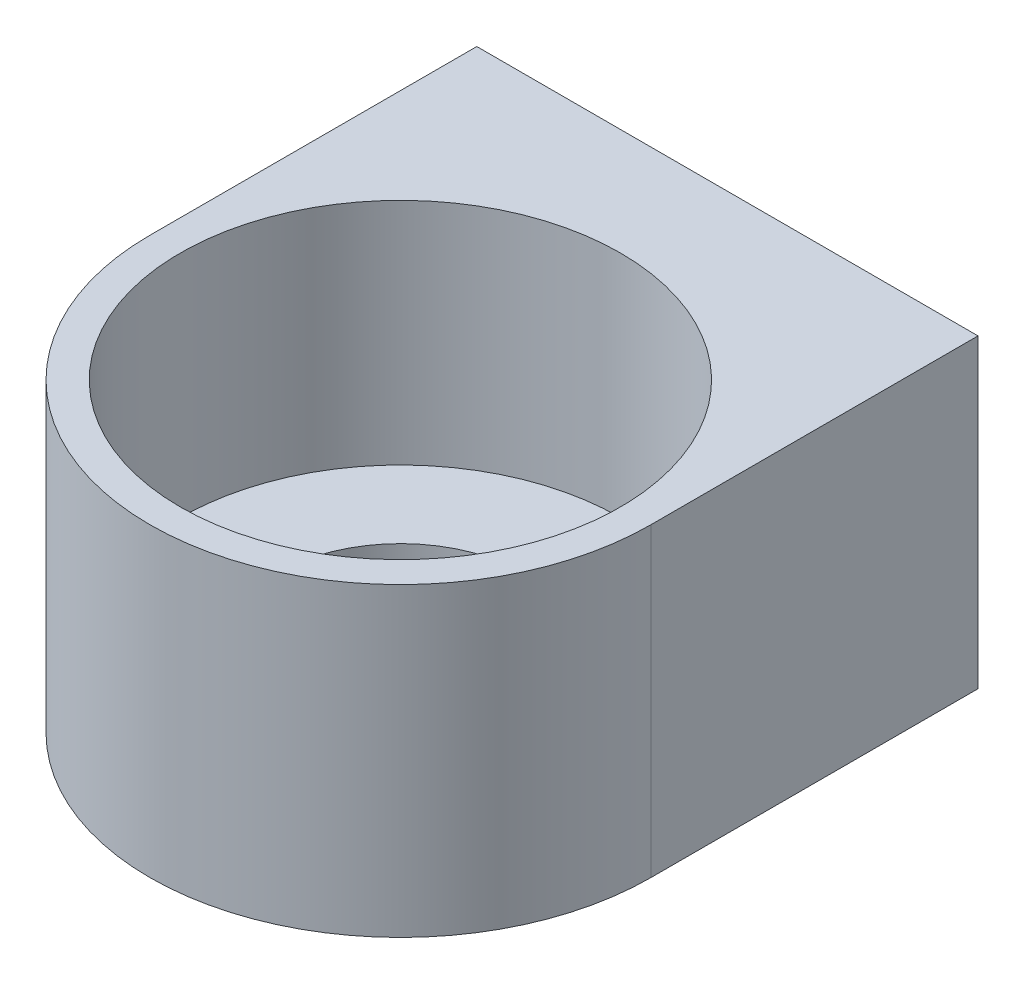
SolidWorks part; units mm, degrees
ref_plane "Front Plane" through (0, 0, 0) normal (0, 0, 1) x (1, 0, 0)
ref_plane "Top Plane" through (0, 0, 0) normal (0, 1, 0) x (1, 0, 0)
ref_plane "Right Plane" through (0, 0, 0) normal (1, 0, 0) x (0, 0, -1)
sketch "Sketch1" plane through (0, 0, 0) normal (0, 1, 0) x (1, 0, 0)
  line L0 (0, 21.4) -> (0, 16.4) construction
  line L2 (-16.4, 0) -> (-16.4, 21.4)
  line L3 (-16.4, 21.4) -> (16.4, 21.4)
  line L4 (16.4, 0) -> (16.4, 21.4)
  circle A0 centre (0, 0) radius 8.1
  circle A1 centre (0, 0) radius 14.4 construction
  arc A2 (-16.4, 0) -> (16.4, 0) centre (0, 0) ccw
  arc A3 (-16.4, 0) -> (16.4, 0) centre (0, 0) cw construction
  dimension "D1" = 16.2
  dimension "D2" = 28.8
  dimension "D3" = 32.8
extrude "Boss-Extrude1" add sketch "Sketch1" along normal blind 100
sketch "Sketch2" plane through (0, 100, 0) normal (0, 1, 0) x (1, 0, 0)
  circle A0 centre (0, 0) radius 14.4
  dimension "D1" = 28.8
extrude "Cut-Extrude1" cut sketch "Sketch2" against normal blind 80
sketch "Sketch3" plane through (0, 100, 0) normal (0, 1, 0) x (1, 0, 0)
  line L0 (0, 14.4) -> (-16.4, 14.4) construction
  line L1 (-16.4, 21.4) -> (-16.4, 0) construction
  line L2 (-16.4, 14.4) -> (-16.4, 0) construction
  line L3 (0, 14.4) -> (0, -16.4) construction
  line L4 (-16.4, 0) -> (-16.4, 14.4)
  line L5 (-16.4, 14.4) -> (16.4, 14.4)
  line L6 (16.4, 0) -> (16.4, 14.4)
  circle A0 centre (0, 0) radius 14.4 construction
  circle A1 centre (0, 0) radius 14.4 construction
  arc A3 (-16.4, 0) -> (16.4, 0) centre (0, 0) ccw
extrude "Cut-Extrude2" cut sketch "Sketch3" against normal blind 80
sketch "Sketch4" plane through (0, 20, 0) normal (0, 1, 0) x (1, 0, 0)
  circle A0 centre (0, 0) radius 14.4
  dimension "D1" = 28.8
extrude "Cut-Extrude3" cut sketch "Sketch4" against normal blind 15
sketch "Sketch8" plane through (0, 0, -14.4) normal (0, 0, 1) x (1, 0, 0)
  line L1 (-16.4, 100) -> (16.4, 100)
  line L2 (-16.4, 100) -> (-16.4, 20)
  line L3 (-16.4, 20) -> (16.4, 20)
  line L4 (16.4, 100) -> (16.4, 20)
extrude "Cut-Extrude4" cut sketch "Sketch8" against normal through all
sketch "Sketch9" plane through (0, 20, 0) normal (0, 1, 0) x (1, 0, 0)
  line L0 (0, 21.4) -> (0, 14.4) construction
  line L1 (-16.4, 21.4) -> (16.4, 21.4) construction
  circle A0 centre (-11.3669, 16.1762) radius 4.1
  circle A1 centre (0, 0) radius 14.4 construction
  circle A2 centre (0, 0) radius 14.4 construction
  point P2 (0, 0)
  dimension "D1" = 8.2
extrude "Cut-Extrude5" cut sketch "Sketch9" against normal blind 3.1 from offset 2 offset against normal yes
mirror "Mirror1" about plane through (0, 0, 0) normal (1, 0, 0) of "Cut-Extrude5"
